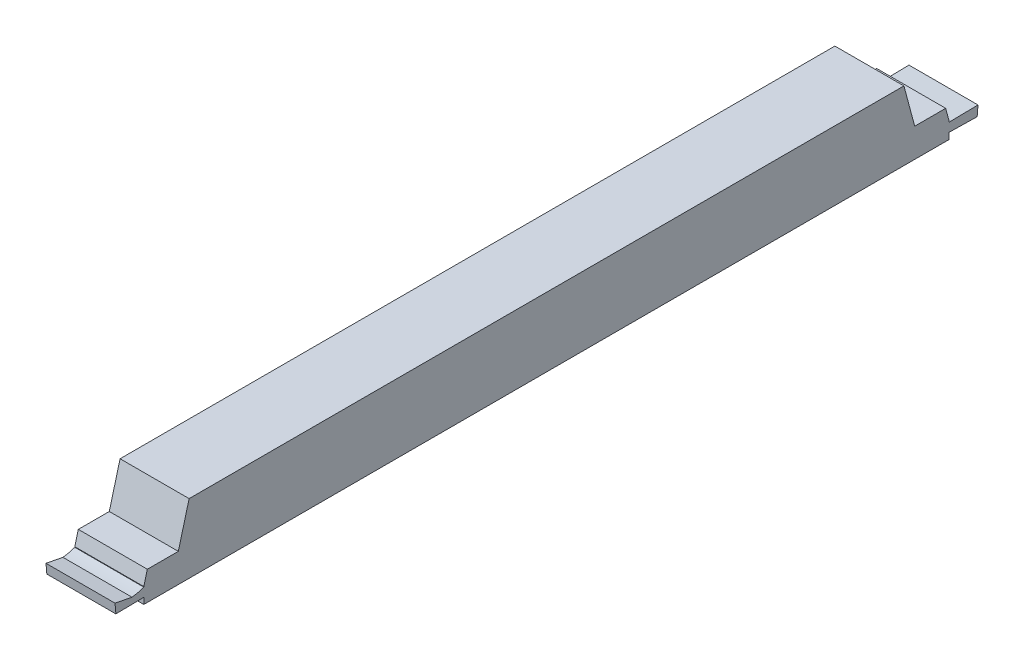
SolidWorks part; units mm, degrees
ref_plane "Front Plane" through (0, 0, 0) normal (0, 0, 1) x (1, 0, 0)
ref_plane "Top Plane" through (0, 0, 0) normal (0, 1, 0) x (1, 0, 0)
ref_plane "Right Plane" through (0, 0, 0) normal (1, 0, 0) x (0, 0, -1)
sketch "Sketch1" plane through (0, 0, 0) normal (0, 0, 1) x (1, 0, 0)
  line L1 (0, 0) -> (12, 0)
  line L2 (0, 0) -> (0, 12)
  line L3 (0, 12) -> (12, 12)
  line L4 (12, 0) -> (12, 12)
  dimension "D1" = 12
  dimension "D2" = 12
extrude "Extrude1" add sketch "Sketch1" along normal blind 150 contours L3 L4 L1 L2
sketch "Sketch2" plane through (12, 0, 0) normal (1, 0, 0) x (0, 0, -1)
  line L0 (0, 0) -> (-5, 0)
  line L2 (-150, 0) -> (0, 0) construction
  line L3 (-5, 0) -> (-5, 1)
  line L5 (-5, 1) -> (0, 1)
  line L6 (0, 0) -> (0, 12) construction
  line L7 (0, 1) -> (0, 0)
  line L8 (-150, 0) -> (-150, 1)
  line L10 (-150, 0) -> (-150, 12) construction
  line L11 (-150, 1) -> (-145, 1)
  line L12 (-145, 1) -> (-145, 0)
  line L14 (-145, 0) -> (-150, 0)
  dimension "D1" = 1
  dimension "D2" = 5
  dimension "D3" = 1
  dimension "D4" = 5
extrude "Cut-Extrude2" cut sketch "Sketch2" against normal through all contours L5 L7 L0 L3 | L11 L12 L14 L8
sketch "Sketch3" plane through (12, 0, 0) normal (1, 0, 0) x (0, 0, -1)
  line L0 (-150, 1) -> (-145, 1) construction
  line L1 (-150, 1) -> (-150, 12) construction
  line L2 (-150, 2.7) -> (-145, 2.7)
  line L3 (-145, 2.7) -> (-144.3837, 5)
  line L4 (-144.3837, 5) -> (-139, 5)
  line L5 (-139, 5) -> (-137.1244, 12)
  line L6 (-150, 12) -> (0, 12) construction
  line L7 (-137.1244, 12) -> (-150, 12)
  line L8 (-150, 12) -> (-150, 2.7)
  line L9 (-145, 0) -> (-5, 0) construction
  line L10 (0, 2.7) -> (-5, 2.7)
  line L11 (0, 1) -> (0, 12) construction
  line L12 (-5, 2.7) -> (-5.6163, 5)
  line L13 (-5.6163, 5) -> (-11, 5)
  line L14 (-11, 5) -> (-12.8756, 12)
  line L15 (-12.8756, 12) -> (0, 12)
  line L16 (0, 12) -> (0, 2.7)
  line L17 (0, 2.7) -> (-0.0409, 2.8499)
  line L19 (-5, 1) -> (0, 1) construction
  dimension "D1" = 1.7
  dimension "D2" = 5
  dimension "D3" = 105
  dimension "D4" = 5
  dimension "D5" = 11
  dimension "D6" = 105
  dimension "D7" = 5
  dimension "D8" = 5
  dimension "D9" = 11
  dimension "D10" = 1.7
extrude "Cut-Extrude3" cut sketch "Sketch3" against normal through all contours L10 L12 L13 L14 L15 L16 | L5 L7 L8 L2 L3 L4
sketch "Sketch4" plane through (12, 0, 0) normal (1, 0, 0) x (0, 0, -1)
  line L0 (-145, 1) -> (-145, 1.0873)
  line L1 (-145, 1.0873) -> (-150, 1)
  line L2 (-150, 1) -> (-145, 1)
  line L3 (-145, 2.7) -> (-145, 2.6127)
  line L4 (-145, 2.6127) -> (-150, 2.7)
  line L5 (-150, 2.7) -> (-145, 2.7)
  line L6 (-145, 2.7) -> (-145.0111, 2.6952)
  line L7 (-5, 2.7) -> (-5, 2.6127)
  line L8 (-5, 2.6127) -> (0, 2.7)
  line L9 (0, 2.7) -> (-5, 2.7)
  line L10 (-5, 1) -> (-5, 1.0873)
  line L11 (-5, 1.0873) -> (0, 1)
  line L12 (0, 1) -> (-5, 1)
  dimension "D1" = 1
  dimension "D2" = 1
  dimension "D3" = 1
  dimension "D4" = 1
extrude "Cut-Extrude4" cut sketch "Sketch4" against normal through all contours L1 L2 L0 | L3 L4 L5 | L8 L9 L7 | L11 L12 L10
sketch "Sketch5" plane through (12, 0, 0) normal (1, 0, 0) x (0, 0, -1)
  line L0 (-150, 2.7) -> (-150, 1)
  line L2 (-150, 1) -> (-149.8515, 1.0026)
  line L3 (-145, 1.0873) -> (-150, 1) construction
  line L4 (-150, 2.7) -> (-145, 2.6127)
  line L5 (-145, 2.6127) -> (-150, 2.7) construction
  line L7 (-147.0551, 2.1276) -> (-150, 2.7)
  line L9 (-149.8515, 1.0026) -> (-150, 2.7)
  line L10 (0, 2.7) -> (-0.1485, 1.0026)
  line L11 (-5, 1.0873) -> (0, 1) construction
  line L12 (-0.1485, 1.0026) -> (0, 1)
  line L13 (0, 1) -> (0, 2.7)
  line L14 (-5, 2.6127) -> (0, 2.7) construction
  line L17 (-2.9449, 2.1276) -> (0, 2.7)
  arc A0 (-147.0551, 2.1276) -> (-145, 2.6127) centre (-147.8495, 10.088) ccw
  arc A1 (-2.9449, 2.1276) -> (-4.3091, 1.9719) centre (-4.5309, 9.9688) cw
  dimension "D7" = 8
  dimension "D9" = 8
  dimension "D1" = 5
  dimension "D2" = 3
  dimension "D3" = 10
  dimension "D4" = 5
  dimension "D5" = 3
  dimension "D6" = 10
extrude "Cut-Extrude5" cut sketch "Sketch5" against normal through all
